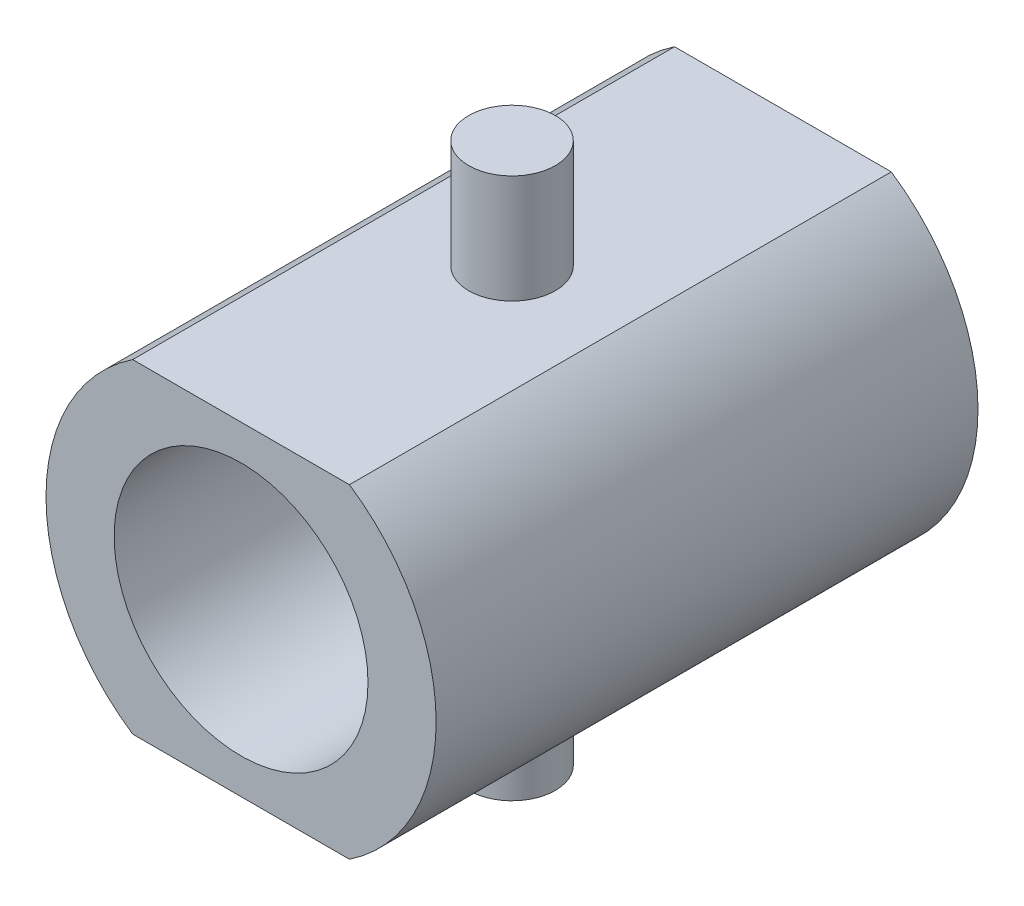
SolidWorks part; units mm, degrees
ref_plane "Plan de face" through (0, 0, 0) normal (0, 0, 1) x (1, 0, 0)
ref_plane "Plan de dessus" through (0, 0, 0) normal (0, 1, 0) x (1, 0, 0)
ref_plane "Plan de droite" through (0, 0, 0) normal (1, 0, 0) x (0, 0, -1)
sketch "Esquisse1" plane through (0, 0, 0) normal (0, 0, 1) x (1, 0, 0)
  line L0 (-15, 25) -> (15, -25) construction
  line L1 (-15, 25) -> (15, 25) construction
  line L2 (-15, 25) -> (-15, -25) construction
  line L3 (-15, -25) -> (15, -25) construction
  line L4 (15, 25) -> (15, -25) construction
  line L5 (15, -25) -> (15.3352, -24.9441) construction
  line L6 (-25, 37.4166) -> (25, 37.4166)
  line L7 (0, 0) -> (68.975, 0) construction
  line L8 (-25, -37.4166) -> (25, -37.4166)
  circle A0 centre (0, 0) radius 29.281
  circle A1 centre (0, 0) radius 45
  dimension "D3" = 90
  dimension "D1" = 30
  dimension "D2" = 50
  dimension "D4" = 50
extrude "Boss.-Extru.1" add sketch "Esquisse1" along normal blind 125 contours L6 A1 L8 A0
sketch "Esquisse2" plane through (0, 37.4166, 0) normal (0, 1, 0) x (1, 0, 0)
  line L0 (25, 0) -> (-25, -125) construction
  circle A0 centre (0, -62.5) radius 10
  dimension "D1" = 20
extrude "Boss.-Extru.2" add sketch "Esquisse2" along normal blind 25
mirror "Symétrie1" about plane through (0, 0, 0) normal (0, 1, 0) of "Boss.-Extru.2"
